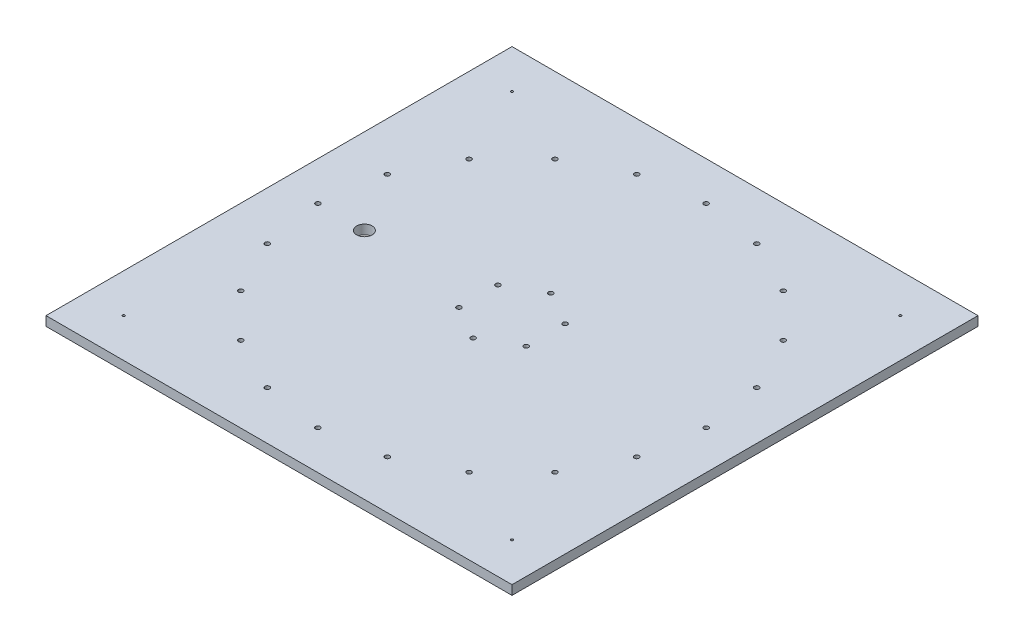
SolidWorks part; units mm, degrees
ref_plane "Front Plane" through (0, 0, 0) normal (0, 0, 1) x (1, 0, 0)
ref_plane "Top Plane" through (0, 0, 0) normal (0, 1, 0) x (1, 0, 0)
ref_plane "Right Plane" through (0, 0, 0) normal (1, 0, 0) x (0, 0, -1)
sketch "Sketch1" plane through (0, 0, 0) normal (0, 1, 0) x (1, 0, 0)
  line L1 (-300, 300) -> (300, 300)
  line L2 (-300, 300) -> (-300, -300)
  line L3 (-300, -300) -> (300, -300)
  line L4 (300, 300) -> (300, -300)
  line L5 (0, 455.7448) -> (0, -379.735) construction
  line L6 (-500.382, 0) -> (488.0909, 0) construction
  circle A6 centre (0, 250) radius 3
  circle A7 centre (77.2542, 237.7641) radius 3
  circle A8 centre (146.9463, 202.2542) radius 3
  circle A9 centre (202.2542, 146.9463) radius 3
  circle A10 centre (237.7641, 77.2542) radius 3
  circle A11 centre (250, 0) radius 3
  circle A12 centre (237.7641, -77.2542) radius 3
  circle A13 centre (202.2542, -146.9463) radius 3
  circle A14 centre (146.9463, -202.2542) radius 3
  circle A15 centre (77.2542, -237.7641) radius 3
  circle A16 centre (0, -250) radius 3
  circle A17 centre (-77.2542, -237.7641) radius 3
  circle A18 centre (-146.9463, -202.2542) radius 3
  circle A19 centre (-202.2542, -146.9463) radius 3
  circle A20 centre (-237.7641, -77.2542) radius 3
  circle A21 centre (-250, 0) radius 3
  circle A22 centre (-237.7641, 77.2542) radius 3
  circle A23 centre (-202.2542, 146.9463) radius 3
  circle A24 centre (-146.9463, 202.2542) radius 3
  circle A25 centre (-77.2542, 237.7641) radius 3
  circle A26 centre (0, 50) radius 3
  circle A27 centre (43.3013, 25) radius 3
  circle A28 centre (43.3013, -25) radius 3
  circle A29 centre (0, -50) radius 3
  circle A30 centre (-43.3013, -25) radius 3
  circle A31 centre (-43.3013, 25) radius 3
  circle A32 centre (-250, 250) radius 1.5
  circle A33 centre (-190, 0) radius 10
  circle A34 centre (250, 250) radius 1.5
  circle A35 centre (250, -250) radius 1.5
  circle A36 centre (-250, -250) radius 1.5
  point P67 (0, 0)
  point P79 (0, 0)
  dimension "D3" = 20
  dimension "D4" = 190
  dimension "D6" = 50
  dimension "D7" = 6
  dimension "D10" = 6
  dimension "D5" = 3
  dimension "D1" = 600
  dimension "D2" = 600
  dimension "D9" = 50
  dimension "D8" = 20
  dimension "D11" = 6
extrude "Boss-Extrude1" add sketch "Sketch1" along normal blind 12
